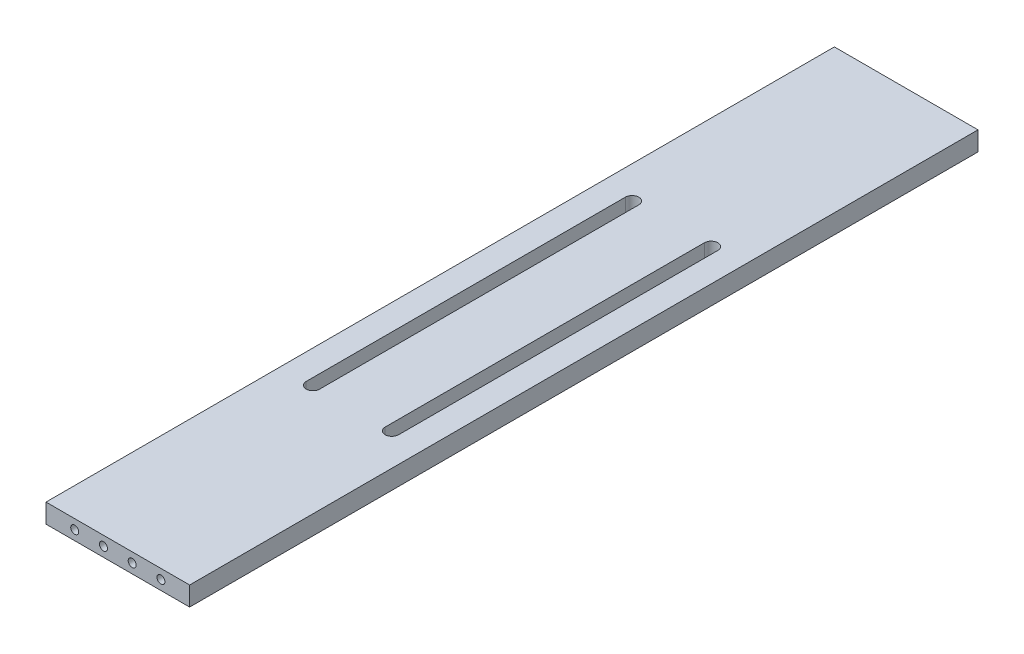
SolidWorks part; units mm, degrees
material "Сплав 2024"
ref_plane "Спереди" through (0, 0, 0) normal (0, 0, 1) x (1, 0, 0)
ref_plane "Сверху" through (0, 0, 0) normal (0, 1, 0) x (1, 0, 0)
ref_plane "Справа" through (0, 0, 0) normal (1, 0, 0) x (0, 0, -1)
sketch "Эскиз1" plane through (0, 0, 0) normal (0, 1, 0) x (1, 0, 0)
  line L2 (-15.9099, 15.9099) -> (15.9099, -15.9099) construction
  line L3 (15.9099, 15.9099) -> (-15.9099, -15.9099) construction
  line L4 (-22.5, 0) -> (-22.5, -247)
  line L5 (-22.5, -247) -> (22.5, -247)
  line L6 (22.5, 0) -> (22.5, -247)
  line L7 (-22.5, 0) -> (22.5, 0)
  dimension "D1" = 247
  dimension "D2" = 45
  dimension "D3" = 45
extrude "Бобышка-Вытянуть1" add sketch "Эскиз1" along normal blind 6
sketch "Эскиз2" plane through (0, 6, 0) normal (0, 1, 0) x (1, 0, 0)
  line L2 (0, 0) -> (0, -247) construction
  line L3 (-22.5, -247) -> (22.5, -247) construction
  line L4 (-12.3744, -135.8744) -> (12.3744, -111.1256) construction
  line L5 (-12.3744, -73.5) -> (-12.3744, -173.5) construction
  line L6 (-10.2744, -73.5) -> (-10.2744, -173.5)
  line L7 (-14.4744, -73.5) -> (-14.4744, -173.5)
  line L8 (-12.3744, -111.1256) -> (12.3744, -135.8744) construction
  line L9 (12.3744, -73.5) -> (12.3744, -173.5) construction
  line L10 (10.2744, -73.5) -> (10.2744, -173.5)
  line L11 (14.4744, -73.5) -> (14.4744, -173.5)
  line L13 (-22.5, -123.5) -> (22.5, -123.5) construction
  line L14 (-22.5, 0) -> (-22.5, -247) construction
  line L15 (22.5, -247) -> (22.5, 0) construction
  circle A0 centre (0, -123.5) radius 6 construction
  circle A1 centre (0, -123.5) radius 17.5 construction
  arc A2 (-10.2744, -73.5) -> (-14.4744, -73.5) centre (-12.3744, -73.5) ccw
  arc A3 (-14.4744, -173.5) -> (-10.2744, -173.5) centre (-12.3744, -173.5) ccw
  arc A4 (10.2744, -73.5) -> (14.4744, -73.5) centre (12.3744, -73.5) cw
  arc A5 (14.4744, -173.5) -> (10.2744, -173.5) centre (12.3744, -173.5) cw
  point P13 (12.3744, -123.5)
  point P18 (-12.3744, -123.5)
  point P37 (0, -123.5)
  dimension "D1" = 12
  dimension "D2" = 35
  dimension "D4" = 2.1
  dimension "D3" = 45
  dimension "D5" = 100
hole_wizard "Цековка для  винта с полукруглой головкой M31" [suppressed] positions "Эскиз4" profile "Эскиз5" counterbore size "M3" standard "Ansi Metric"
sketch "Эскиз4" plane through (0, 6, 0) normal (0, 1, 0) x (1, 0, 0)
  line L2 (-36.6046, 36.6046) -> (36.6046, -36.6046) construction
  line L3 (-12.3744, -12.3744) -> (12.3744, 12.3744) construction
  circle A0 centre (0, 0) radius 6 construction
  point P0 (-4.2426, 4.2426)
  point P6 (-4.2426, -4.2426)
  point P10 (4.2426, -4.2426)
  point P12 (4.2426, 4.2426)
sketch "Эскиз5" plane through (-4.2426, 6, -4.2426) normal (1, 0, 0) x (0, 0, 1)
  line L0 (0, 0) -> (0, 6)
  line L1 (0, 6) -> (1.7, 6)
  line L3 (1.7, 6) -> (1.7, 2)
  line L4 (1.7, 2) -> (3.35, 2)
  line L5 (3.35, 2) -> (3.35, 0)
  line L7 (3.35, 0) -> (0, 0)
  line L11 (0, -6.35) -> (0, 107.95) construction
  dimension "Диаметр сквозного отверстия" = 3.4
  dimension "Глубина сквозного отверстия" = 6
  dimension "Диаметр цековки" = 6.7
  dimension "Глубина цековки" = 2
hole_wizard "Отверстие обработанное метчиком M4x0.71" [suppressed] positions "Эскиз7" profile "Эскиз6" tap size "M4x0.7" standard "Ansi Metric"
sketch "Эскиз7" [suppressed] plane through (0, 4, 0) normal (0, 1, 0) x (1, 0, 0)
  line L0 (22.5, 0) -> (-22.5, 0) construction
  line L1 (0, 22.5) -> (0, -22.5) construction
  circle A0 centre (0, 0) radius 19.25 construction
  point P0 (-19.25, 0)
  point P6 (0, -19.25)
  point P10 (19.25, 0)
  point P12 (0, 19.25)
sketch "Эскиз6" plane through (-19.25, 4, 0) normal (1, 0, 0) x (0, 0, 1)
  line L0 (0, 0) -> (0, 4)
  line L1 (0, 4) -> (1.65, 4)
  line L2 (1.65, 4) -> (1.65, 0)
  line L5 (1.65, 0) -> (0, 0)
  line L11 (0, -6.35) -> (0, 107.95) construction
  dimension "Диаметр резьбы" = 3.3
  dimension "Глубина проходного сверла" = 4
extrude "Вырез-Вытянуть1" cut sketch "Эскиз2" against normal through all
sketch "Эскиз8" plane through (0, 0, 247) normal (0, 0, 1) x (1, 0, 0)
  line L0 (-22.5, 3) -> (22.5, 3) construction
  line L1 (-22.5, 6) -> (-22.5, 0) construction
  line L2 (22.5, 6) -> (22.5, 0) construction
  line L3 (-13.5, 6) -> (-13.5, 0) construction
  line L6 (-4.5, 6) -> (-4.5, 0) construction
  line L7 (4.5, 6) -> (4.5, 0) construction
  line L8 (13.5, 6) -> (13.5, 0) construction
  dimension "D1" = 45
  dimension "D2" = 9
  dimension "D3" = 9
  dimension "D4" = 9
  dimension "D5" = 9
hole_wizard "Отверстие обработанное метчиком M3x0.51" positions "Эскиз10" profile "Эскиз9" tap size "M3x0.5" standard "Ansi Metric"
sketch "Эскиз10" plane through (0, 0, 247) normal (0, 0, 1) x (1, 0, 0)
  line L0 (-13.5, 6) -> (-13.5, 0) construction
  line L1 (-4.5, 6) -> (-4.5, 0) construction
  line L2 (4.5, 6) -> (4.5, 0) construction
  line L3 (13.5, 6) -> (13.5, 0) construction
  point P0 (-13.5, 3)
  point P4 (-4.5, 3)
  point P8 (4.5, 3)
  point P12 (13.5, 3)
sketch "Эскиз9" plane through (-13.5, 3, 247) normal (1, 0, 0) x (0, -1, 0)
  line L0 (0, 0) -> (0, 9.2511)
  line L1 (0, 9.2511) -> (1.25, 8.5)
  line L2 (1.25, 8.5) -> (1.25, 0)
  line L5 (1.25, 0) -> (0, 0)
  line L10 (0, 9.2511) -> (-1.25, 8.5) construction
  line L11 (0, -6.35) -> (0, 107.95) construction
  dimension "Диаметр сверла" = 2.5
  dimension "Глубина сверла" = 8.5
  dimension "Угол заточки сверла" = 118
cosmetic thread "Отверстие резьбы1" parameters "D1"=6, "D2"=3
cosmetic thread "Отверстие резьбы2" parameters "D1"=6, "D2"=3
cosmetic thread "Отверстие резьбы3" parameters "D1"=6, "D2"=3
cosmetic thread "Отверстие резьбы4" parameters "D1"=6, "D2"=3
hole_wizard "Отверстие обработанное метчиком M3x0.52" positions "Эскиз12" profile "Эскиз11" tap size "M3x0.5" standard "Ansi Metric"
sketch "Эскиз12" plane through (0, 0, 0) normal (0, 0, -1) x (-1, 0, 0)
  line L0 (-13.5, 6) -> (-13.5, 0) construction
  line L1 (-4.5, 6) -> (-4.5, 0) construction
  line L2 (4.5, 6) -> (4.5, 0) construction
  line L3 (13.5, 6) -> (13.5, 0) construction
  point P0 (-13.5, 3)
  point P4 (-4.5, 3)
  point P8 (4.5, 3)
  point P12 (13.5, 3)
sketch "Эскиз11" plane through (13.5, 3, 0) normal (1, 0, 0) x (0, 1, 0)
  line L0 (0, 0) -> (0, 9.2511)
  line L1 (0, 9.2511) -> (1.25, 8.5)
  line L2 (1.25, 8.5) -> (1.25, 0)
  line L5 (1.25, 0) -> (0, 0)
  line L10 (0, 9.2511) -> (-1.25, 8.5) construction
  line L11 (0, -6.35) -> (0, 107.95) construction
  dimension "Диаметр сверла" = 2.5
  dimension "Глубина сверла" = 8.5
  dimension "Угол заточки сверла" = 118
cosmetic thread "Отверстие резьбы5" parameters "D1"=6, "D2"=3
cosmetic thread "Отверстие резьбы6" parameters "D1"=6, "D2"=3
cosmetic thread "Отверстие резьбы7" parameters "D1"=6, "D2"=3
cosmetic thread "Отверстие резьбы8" parameters "D1"=6, "D2"=3
equation "\"D2@Эскиз8\"=\"D1@Эскиз8\"/5"
equation "\"D3@Эскиз8\"=\"D2@Эскиз8\""
equation "\"D4@Эскиз8\"=\"D2@Эскиз8\""
equation "\"D5@Эскиз8\"=\"D2@Эскиз8\""
